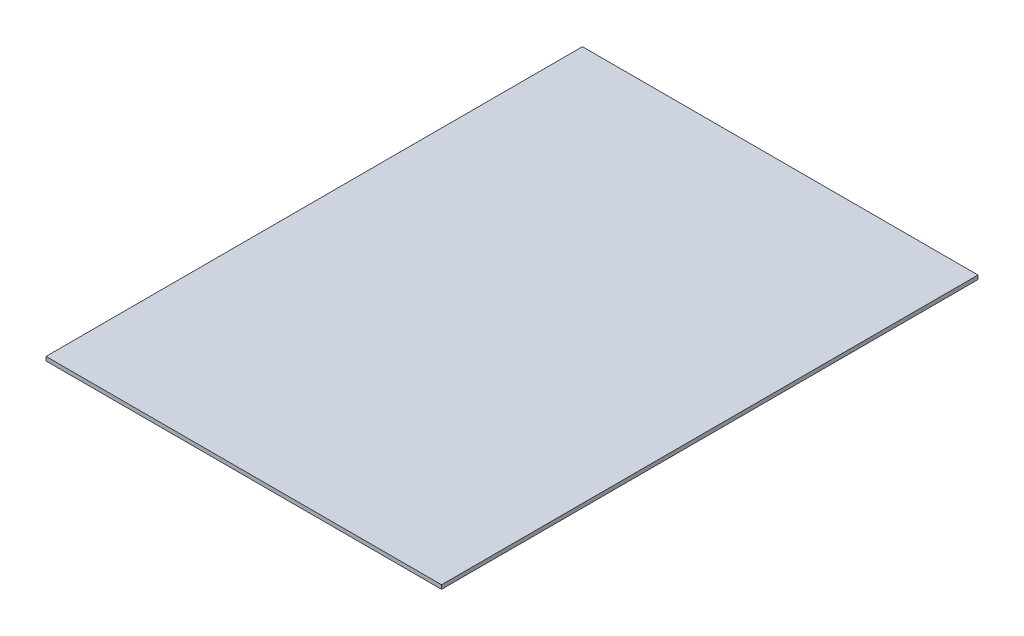
SolidWorks part; units mm, degrees
ref_plane "Front Plane" through (0, 0, 0) normal (0, 0, 1) x (1, 0, 0)
ref_plane "Top Plane" through (0, 0, 0) normal (0, 1, 0) x (1, 0, 0)
ref_plane "Right Plane" through (0, 0, 0) normal (1, 0, 0) x (0, 0, -1)
sketch "Sketch1" plane through (0, 0, 0) normal (0, 1, 0) x (1, 0, 0)
  line L1 (-150, 203.45) -> (150, 203.45)
  line L2 (-150, 203.45) -> (-150, -203.45)
  line L3 (-150, -203.45) -> (150, -203.45)
  line L4 (150, 203.45) -> (150, -203.45)
  line L5 (-150, 203.45) -> (150, -203.45) construction
  line L6 (-150, -203.45) -> (150, 203.45) construction
  point P0 (0, 0)
  dimension "D1" = 300
  dimension "D2" = 406.9
extrude "Boss-Extrude1" add sketch "Sketch1" along normal blind 3
